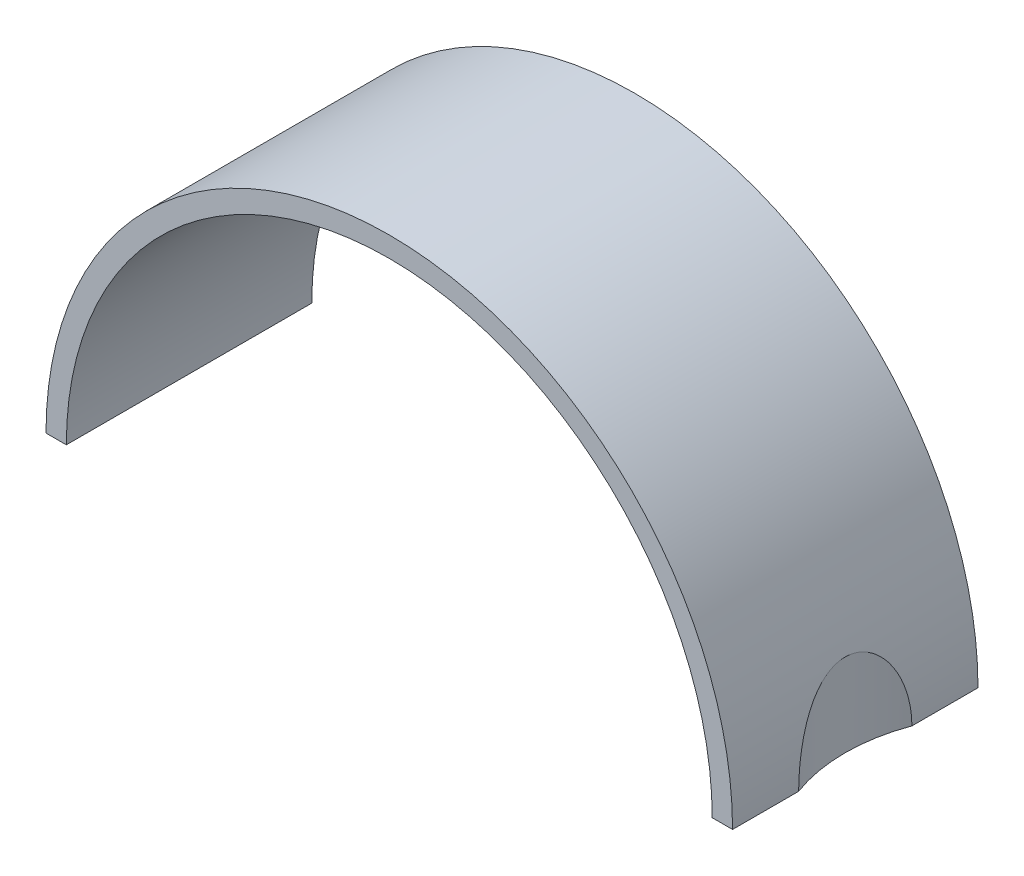
SolidWorks part; units mm, degrees
ref_plane "Płaszczyzna przednia" through (0, 0, 0) normal (0, 0, 1) x (1, 0, 0)
ref_plane "Płaszczyzna górna" through (0, 0, 0) normal (0, 1, 0) x (1, 0, 0)
ref_plane "Płaszczyzna prawa" through (0, 0, 0) normal (1, 0, 0) x (0, 0, -1)
sketch "Szkic1" plane through (0, 0, 0) normal (0, 0, 1) x (1, 0, 0)
  line L0 (33.75, 0) -> (31.75, 0)
  line L1 (-31.75, 0) -> (-33.75, 0)
  arc A0 (31.75, 0) -> (-31.75, 0) centre (0, 0) ccw
  arc A1 (33.75, 0) -> (-33.75, 0) centre (0, 0) ccw
  dimension "D1" = 63.5
  dimension "D2" = 67.5
extrude "Dodanie-wyciągnięcie1" add sketch "Szkic1" along normal mid plane 24.13
sketch "Szkic2" plane through (0, 0, 0) normal (0, -1, 0) x (-1, 0, 0)
  line L1 (-33.75, 5.5678) -> (-33.75, 0)
  line L8 (-33.75, -5.5678) -> (-33.75, 0)
  line L9 (-33.75, -12.065) -> (-33.75, 12.065) construction
  arc A2 (-33.75, -5.5678) -> (-33.75, 5.5678) centre (-48.75, 0) ccw
  dimension "D1" = 15
extrude "Wytnij-wyciągnięcie1" cut sketch "Szkic2" against normal through all
mirror "Lustro1" about plane through (0, 0, 0) normal (1, 0, 0) of "Wytnij-wyciągnięcie1"
